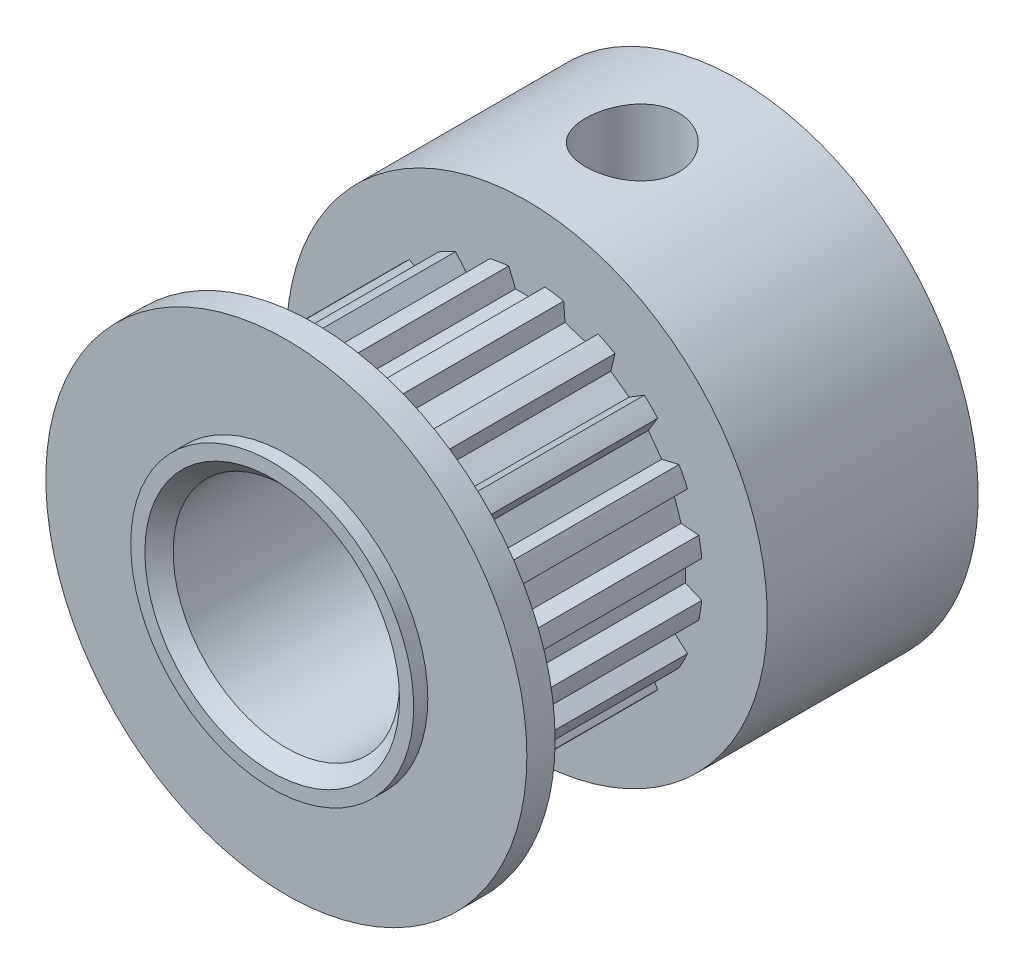
SolidWorks part; units mm, degrees
ref_plane "Alzado" through (0, 0, 0) normal (0, 0, 1) x (1, 0, 0)
ref_plane "Planta" through (0, 0, 0) normal (0, 1, 0) x (1, 0, 0)
ref_plane "Vista lateral" through (0, 0, 0) normal (1, 0, 0) x (0, 0, -1)
sketch "Croquis1" plane through (0, 0, 0) normal (0, 1, 0) x (1, 0, 0)
  line L0 (8.5, -14.95) -> (0, -14.95)
  line L1 (0, -14.95) -> (0, -15.95)
  line L2 (0, -15.95) -> (8.5, -15.95)
  line L3 (8.5, -15.95) -> (8.5, -14.95)
  line L4 (0, -14.95) -> (0, -15.95) construction
revolve "Revolución1" add sketch "Croquis1" angle 360 about L4
sketch "Croquis2" plane through (0, 0, 14.95) normal (0, 0, -1) x (-1, 0, 0)
  line L0 (-1.3007, -6.0774) -> (-1.3501, -5.4495)
  line L1 (-1.3501, -5.4495) -> (-2.1109, -5.2023)
  line L2 (-2.1109, -5.2023) -> (-2.5199, -5.6812)
  line L3 (-3.115, -5.378) -> (-2.968, -4.7656)
  line L4 (-2.968, -4.7656) -> (-3.6152, -4.2954)
  line L5 (-3.6152, -4.2954) -> (-4.1522, -4.6244)
  line L6 (-4.6244, -4.1522) -> (-4.2954, -3.6152)
  line L7 (-4.2954, -3.6152) -> (-4.7656, -2.968)
  line L8 (-4.7656, -2.968) -> (-5.378, -3.115)
  line L9 (-5.6812, -2.5199) -> (-5.2023, -2.1109)
  line L10 (-5.2023, -2.1109) -> (-5.4495, -1.3501)
  line L11 (-5.4495, -1.3501) -> (-6.0774, -1.3007)
  line L12 (-6.1819, -0.641) -> (-5.6, -0.4)
  line L13 (-5.6, -0.4) -> (-5.6, 0.4)
  line L14 (-5.6, 0.4) -> (-6.1819, 0.641)
  line L15 (-6.0774, 1.3007) -> (-5.4495, 1.3501)
  line L16 (-5.4495, 1.3501) -> (-5.2023, 2.1109)
  line L17 (-5.2023, 2.1109) -> (-5.6812, 2.5199)
  line L18 (-5.378, 3.115) -> (-4.7656, 2.968)
  line L19 (-4.7656, 2.968) -> (-4.2954, 3.6152)
  line L20 (-4.2954, 3.6152) -> (-4.6244, 4.1522)
  line L21 (-4.1522, 4.6244) -> (-3.6152, 4.2954)
  line L22 (-3.6152, 4.2954) -> (-2.968, 4.7656)
  line L23 (-2.968, 4.7656) -> (-3.115, 5.378)
  line L24 (-2.5199, 5.6812) -> (-2.1109, 5.2023)
  line L25 (-2.1109, 5.2023) -> (-1.3501, 5.4495)
  line L26 (-1.3501, 5.4495) -> (-1.3007, 6.0774)
  line L27 (-0.641, 6.1819) -> (-0.4, 5.6)
  line L28 (-0.4, 5.6) -> (0.4, 5.6)
  line L29 (0.4, 5.6) -> (0.641, 6.1819)
  line L30 (1.3007, 6.0774) -> (1.3501, 5.4495)
  line L31 (1.3501, 5.4495) -> (2.1109, 5.2023)
  line L32 (2.1109, 5.2023) -> (2.5199, 5.6812)
  line L33 (3.115, 5.378) -> (2.968, 4.7656)
  line L34 (2.968, 4.7656) -> (3.6152, 4.2954)
  line L35 (3.6152, 4.2954) -> (4.1522, 4.6244)
  line L36 (4.6244, 4.1522) -> (4.2954, 3.6152)
  line L37 (4.2954, 3.6152) -> (4.7656, 2.968)
  line L38 (4.7656, 2.968) -> (5.378, 3.115)
  line L39 (5.6812, 2.5199) -> (5.2023, 2.1109)
  line L40 (5.2023, 2.1109) -> (5.4495, 1.3501)
  line L41 (5.4495, 1.3501) -> (6.0774, 1.3007)
  line L42 (6.1819, 0.641) -> (5.6, 0.4)
  line L43 (5.6, 0.4) -> (5.6, -0.4)
  line L44 (5.6, -0.4) -> (6.1819, -0.641)
  line L45 (6.0774, -1.3007) -> (5.4495, -1.3501)
  line L46 (5.4495, -1.3501) -> (5.2023, -2.1109)
  line L47 (5.2023, -2.1109) -> (5.6812, -2.5199)
  line L48 (5.378, -3.115) -> (4.7656, -2.968)
  line L49 (4.7656, -2.968) -> (4.2954, -3.6152)
  line L50 (4.2954, -3.6152) -> (4.6244, -4.1522)
  line L51 (4.1522, -4.6244) -> (3.6152, -4.2954)
  line L52 (3.6152, -4.2954) -> (2.968, -4.7656)
  line L53 (2.968, -4.7656) -> (3.115, -5.378)
  line L54 (2.5199, -5.6812) -> (2.1109, -5.2023)
  line L55 (2.1109, -5.2023) -> (1.3501, -5.4495)
  line L56 (1.3501, -5.4495) -> (1.3007, -6.0774)
  line L57 (0.641, -6.1819) -> (0.4, -5.6)
  line L58 (0.4, -5.6) -> (-0.4, -5.6)
  line L59 (-0.4, -5.6) -> (-0.641, -6.1819)
  arc A0 (-0.641, -6.1819) -> (-1.3007, -6.0774) centre (0, 0) cw
  arc A1 (-2.5199, -5.6812) -> (-3.115, -5.378) centre (0, 0) cw
  arc A2 (-4.1522, -4.6244) -> (-4.6244, -4.1522) centre (0, 0) cw
  arc A3 (-5.378, -3.115) -> (-5.6812, -2.5199) centre (0, 0) cw
  arc A4 (-6.0774, -1.3007) -> (-6.1819, -0.641) centre (0, 0) cw
  arc A5 (-6.1819, 0.641) -> (-6.0774, 1.3007) centre (0, 0) cw
  arc A6 (-5.6812, 2.5199) -> (-5.378, 3.115) centre (0, 0) cw
  arc A7 (-4.6244, 4.1522) -> (-4.1522, 4.6244) centre (0, 0) cw
  arc A8 (-3.115, 5.378) -> (-2.5199, 5.6812) centre (0, 0) cw
  arc A9 (-1.3007, 6.0774) -> (-0.641, 6.1819) centre (0, 0) cw
  arc A10 (0.641, 6.1819) -> (1.3007, 6.0774) centre (0, 0) cw
  arc A11 (2.5199, 5.6812) -> (3.115, 5.378) centre (0, 0) cw
  arc A12 (4.1522, 4.6244) -> (4.6244, 4.1522) centre (0, 0) cw
  arc A13 (5.378, 3.115) -> (5.6812, 2.5199) centre (0, 0) cw
  arc A14 (6.0774, 1.3007) -> (6.1819, 0.641) centre (0, 0) cw
  arc A15 (6.1819, -0.641) -> (6.0774, -1.3007) centre (0, 0) cw
  arc A16 (5.6812, -2.5199) -> (5.378, -3.115) centre (0, 0) cw
  arc A17 (4.6244, -4.1522) -> (4.1522, -4.6244) centre (0, 0) cw
  arc A18 (3.115, -5.378) -> (2.5199, -5.6812) centre (0, 0) cw
  arc A19 (1.3007, -6.0774) -> (0.641, -6.1819) centre (0, 0) cw
extrude "Saliente-Extruir1" add sketch "Croquis2" along normal blind 7.5
ref_plane "Plano1" through (0, 0, 7.45) normal (0, 0, 1) x (1, 0, 0)
sketch "Croquis3" plane through (0, 0, 7.45) normal (0, 0, 1) x (1, 0, 0)
  circle A0 centre (0, 0) radius 8.5
extrude "Saliente-Extruir2" add sketch "Croquis3" against normal blind 7.45
sketch "Croquis4" plane through (0, 0, 15.95) normal (0, 0, 1) x (1, 0, 0)
  circle A0 centre (0, 0) radius 5
extrude "Saliente-Extruir3" add sketch "Croquis4" along normal blind 0.5
hole_wizard "Diámetro de taladro Ø8.0 (8)1" positions "Croquis6" profile "Croquis5" hole size "Ø8.0" standard "Ansi Metric"
sketch "Croquis6" plane through (0, 0, 16.45) normal (0, 0, 1) x (1, 0, 0)
  point P0 (0, 0)
sketch "Croquis5" plane through (0, 0, 16.45) normal (1, 0, 0) x (0, -1, 0)
  line L0 (0, 0) -> (0, 16.45)
  line L1 (0, 16.45) -> (4, 16.45)
  line L2 (4, 16.45) -> (4, 0)
  line L5 (4, 0) -> (0, 0)
  line L11 (0, -6.35) -> (0, 107.95) construction
  dimension "Diámetro de taladro hasta el siguiente" = 8
  dimension "Profundidad de taladro hasta el siguiente" = 16.45
hole_wizard "Taladro de margen para M3.51" positions "Croquis3D1" profile "Croquis7" hole size "M3.5" standard "Ansi Metric"
sketch3d "Croquis3D1"
  point P0 (0, 8.5, 3.725)
sketch "Croquis7" plane through (0, 8.5, 3.725) normal (1, 0, 0) x (0, 0, 1)
  line L0 (0, 0) -> (0, 4.5)
  line L1 (0, 4.5) -> (1.65, 4.5)
  line L2 (1.65, 4.5) -> (1.65, 0)
  line L5 (1.65, 0) -> (0, 0)
  line L11 (0, -6.35) -> (0, 107.95) construction
  dimension "Diámetro de taladro hasta el siguiente" = 3.3
  dimension "Profundidad de taladro hasta el siguiente" = 4.5
chamfer "Chaflán1" distance 0.5 angle 45 2 edges at (4, 0, 0) (4, 0, 16.45)
